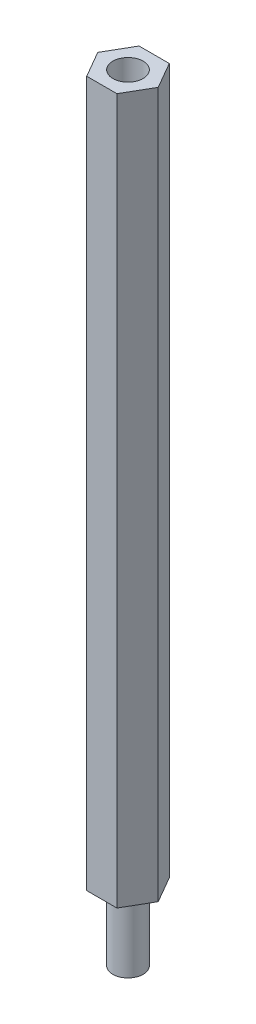
SolidWorks part; units mm, degrees
material "Brass"
ref_plane "Front Plane" through (0, 0, 0) normal (0, 0, 1) x (1, 0, 0)
ref_plane "Top Plane" through (0, 0, 0) normal (0, 1, 0) x (1, 0, 0)
ref_plane "Right Plane" through (0, 0, 0) normal (1, 0, 0) x (0, 0, -1)
sketch "Sketch1" plane through (0, 0, 0) normal (0, 1, 0) x (1, 0, 0)
  line L1 (3, 0) -> (1.5, 2.5981)
  line L2 (1.5, 2.5981) -> (-1.5, 2.5981)
  line L3 (-1.5, 2.5981) -> (-3, 0)
  line L4 (-3, 0) -> (-1.5, -2.5981)
  line L5 (-1.5, -2.5981) -> (1.5, -2.5981)
  line L6 (1.5, -2.5981) -> (3, 0)
  circle A0 centre (0, 0) radius 2.5981 construction
  dimension "D1" = 3
extrude "Boss-Extrude1" add sketch "Sketch1" along normal blind 70
sketch "Sketch2" plane through (0, 70, 0) normal (0, 1, 0) x (1, 0, 0)
  circle A0 centre (0, 0) radius 1.5
  dimension "D1" = 3
extrude "Cut-Extrude1" cut sketch "Sketch2" against normal blind 20
sketch "Sketch3" plane through (0, 0, 0) normal (0, -1, 0) x (-1, 0, 0)
  circle A0 centre (0, 0) radius 1.5
  dimension "D1" = 3
extrude "Boss-Extrude2" add sketch "Sketch3" along normal blind 7
